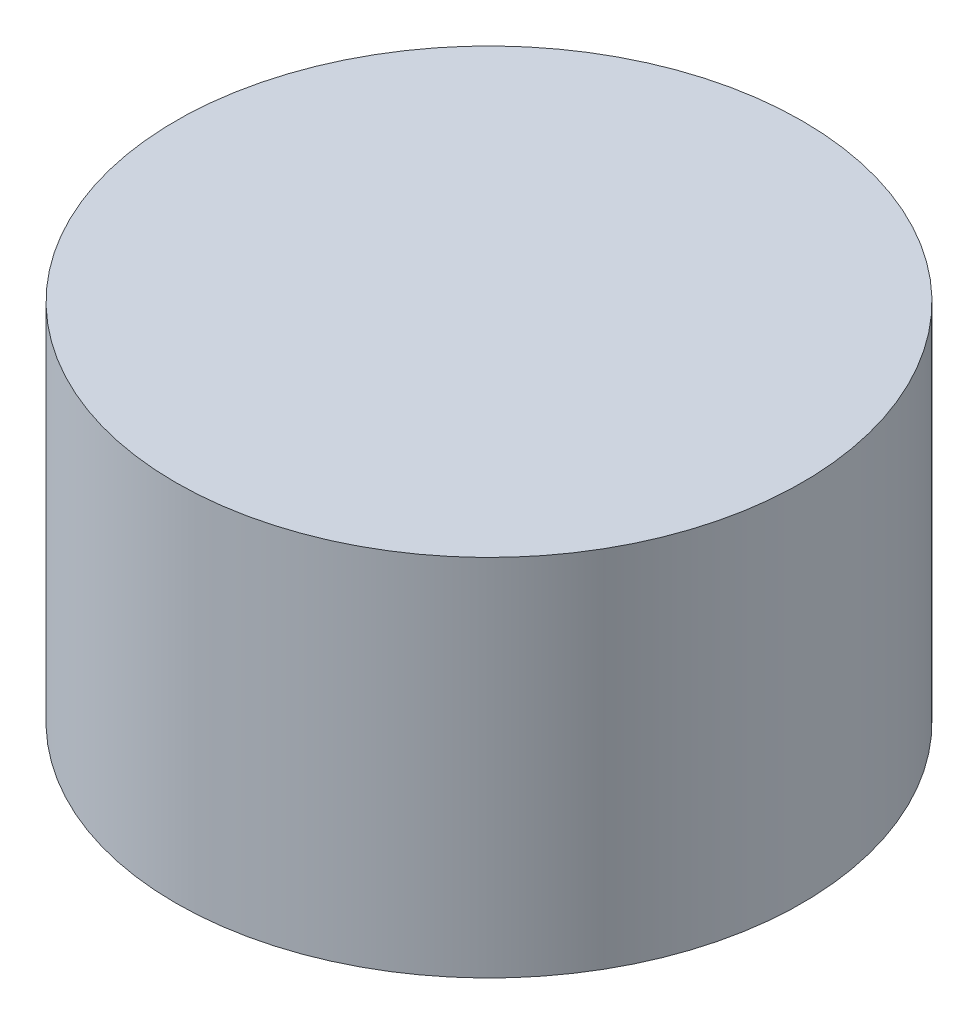
SolidWorks part; units mm, degrees
ref_plane "Front Plane" through (0, 0, 0) normal (0, 0, 1) x (1, 0, 0)
ref_plane "Top Plane" through (0, 0, 0) normal (0, 1, 0) x (1, 0, 0)
ref_plane "Right Plane" through (0, 0, 0) normal (1, 0, 0) x (0, 0, -1)
sketch "Sketch1" plane through (0, 0, 0) normal (0, 1, 0) x (1, 0, 0)
  circle A0 centre (0, 0) radius 4.3
  dimension "D1" = 8.6
extrude "Boss-Extrude1" add sketch "Sketch1" along normal blind 5
